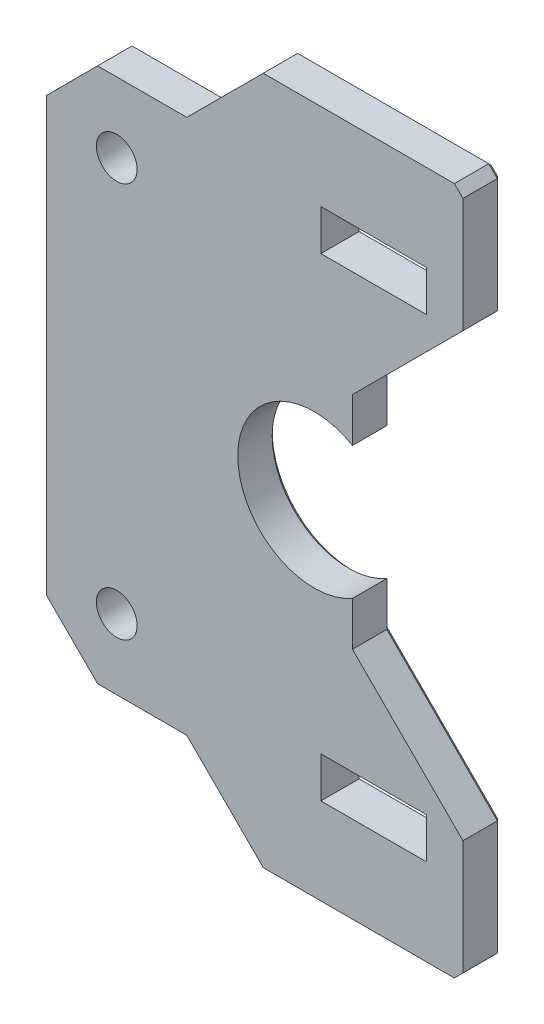
SolidWorks part; units mm, degrees
material "6061-T6 Black anodised"
ref_plane "Front Plane" through (0, 0, 0) normal (0, 0, 1) x (1, 0, 0)
ref_plane "Top Plane" through (0, 0, 0) normal (0, 1, 0) x (1, 0, 0)
ref_plane "Right Plane" through (0, 0, 0) normal (1, 0, 0) x (0, 0, -1)
sketch "Sketch1" plane through (0, 0, 0) normal (0, 0, 1) x (1, 0, 0)
  line L0 (4.675, 21) -> (4.675, -21) construction
  line L1 (-21, 21) -> (21, 21) construction
  line L2 (-21, 21) -> (-21, -21)
  line L3 (-21, -21) -> (21, -21) construction
  line L4 (21, 21) -> (21, -21) construction
  line L5 (-21, 21) -> (21, -21) construction
  line L6 (-21, -21) -> (21, 21) construction
  line L7 (5.55, 21) -> (5.55, -21) construction
  line L8 (3.8, 21) -> (3.8, -21) construction
  line L9 (-10, 0) -> (21, 0) construction
  line L10 (11.675, -17.3319) -> (11.675, -26.325)
  line L11 (3, -8.6569) -> (11.675, -17.3319)
  line L12 (3, -8.6569) -> (3, -5.1962)
  line L14 (11.675, -26.325) -> (21, -17) construction
  line L15 (11.675, -26.325) -> (11, -27)
  line L16 (-10, 21) -> (-21, 21)
  line L17 (-4, -27) -> (11, -27)
  line L18 (-21, -21) -> (-10, -21)
  line L19 (-4, 27) -> (11, 27)
  line L20 (-10, 21) -> (-10, -21) construction
  line L21 (-21, 15.5) -> (-10, 15.5) construction
  line L23 (-10, 21) -> (-4, 27)
  line L24 (-10, -21) -> (-4, -27)
  line L26 (3, 8.6569) -> (11.675, 17.3319)
  line L27 (11.675, 17.3319) -> (11.675, 26.325)
  line L28 (11.675, 26.325) -> (11, 27)
  line L29 (3, 8.6569) -> (3, 5.1962)
  arc A0 (3, 5.1962) -> (3, -5.1962) centre (0, 0) ccw
  circle A2 centre (-15.5, -15.5) radius 1.6
  circle A3 centre (-15.5, 15.5) radius 1.6
  circle A4 centre (10.55, 0) radius 5 construction
  circle A6 centre (0, 0) radius 4 construction
  point P0 (0, 0)
  point P18 (5.55, 0)
  dimension "D4" = 3.2
  dimension "D5" = 10
  dimension "D7" = 8
  dimension "D8" = 6
  dimension "D10" = 4
  dimension "D12" = 3
  dimension "D15" = 27
  dimension "D1" = 42
  dimension "D2" = 4.675
  dimension "D3" = 31
  dimension "D6" = 0.875
  dimension "D9" = 1.75
  dimension "D11" = 45
  dimension "D14" = 27
  dimension "D16" = 10
  dimension "D18" = 7
  dimension "D19" = 4
extrude "Boss-Extrude1" add sketch "Sketch1" along normal blind 3
chamfer "Chamfer6" distance 4 angle 45 2 edges at (-21, 21, 1.5) (-21, -21, 1.5)
chamfer "Chamfer5" distance 0.3 angle 45 20 edges at (3.5, 27, 0) (-13.9, -15.5, 0) (-7, 24, 0) (-13.5, 21, 0) (-21, 0, 0) (-13.5, -21, 0) (-7, -24, 0) (3.5, -27, 0) (-13.9, 15.5, 0) (-19, 19, 0) (-19, -19, 0) (7.3375, 12.9944, 0) (11.675, 21.8284, 0) (11.3375, 26.6625, 0) (11.3375, -26.6625, 0) (11.675, -21.8284, 0) (7.3375, -12.9944, 0) (3, -6.9265, 0) (-6, 0, 0) (3, 6.9265, 0)
sketch "Sketch8" plane through (0, 0, 3) normal (0, 0, 1) x (1, 0, 0)
  line L1 (0.525, 20.2) -> (8.825, 20.2)
  line L2 (0.525, 20.2) -> (0.525, 17)
  line L3 (0.525, 17) -> (8.825, 17)
  line L4 (8.825, 17) -> (8.825, 20.2)
  line L5 (0.525, -17) -> (8.825, -17)
  line L6 (0.525, -17) -> (0.525, -20.2)
  line L7 (0.525, -20.2) -> (8.825, -20.2)
  line L8 (8.825, -17) -> (8.825, -20.2)
  line L9 (4.675, 20.2) -> (4.675, -20.2) construction
  line L10 (0, 0) -> (4.675, 0) construction
  dimension "D1" = 8.3
  dimension "D2" = 4.675
  dimension "D3" = 17
  dimension "D4" = 3.2
extrude "Cut-Extrude1" cut sketch "Sketch8" against normal through all
